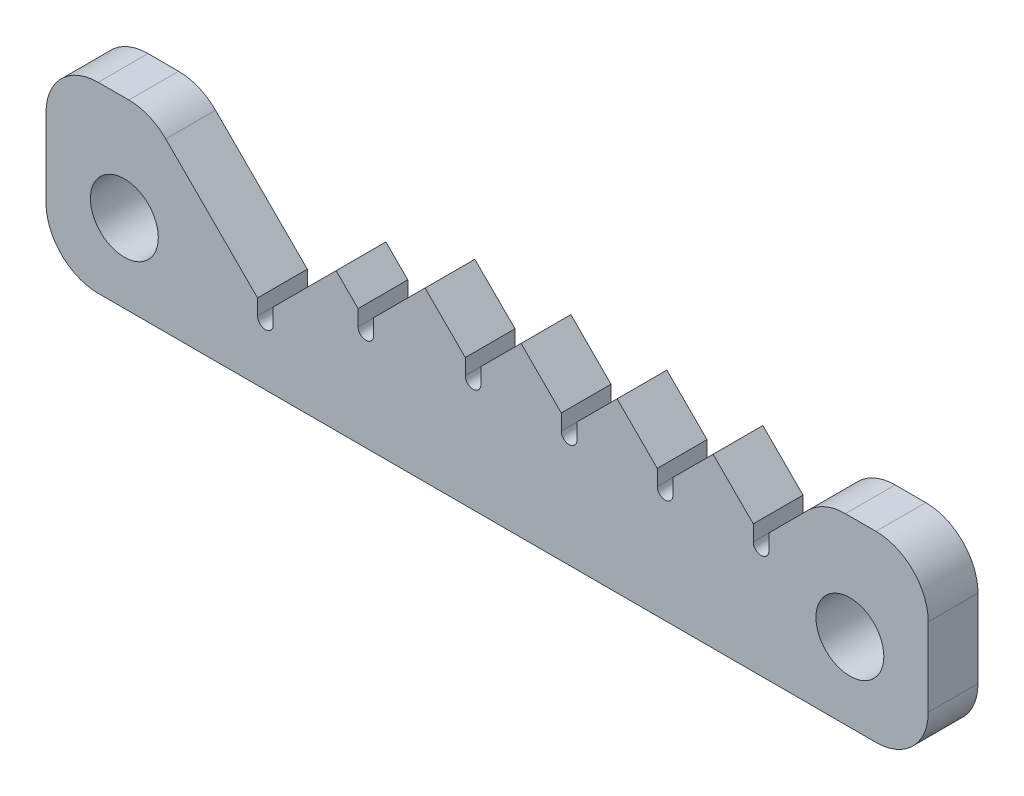
SolidWorks part; units mm, degrees
ref_plane "Alzado" through (0, 0, 0) normal (0, 0, 1) x (1, 0, 0)
ref_plane "Planta" through (0, 0, 0) normal (0, 1, 0) x (1, 0, 0)
ref_plane "Vista lateral" through (0, 0, 0) normal (1, 0, 0) x (0, 0, -1)
sketch "Croquis9" plane through (0, 0, 0) normal (0, 0, 1) x (1, 0, 0)
  line L57 (-5, 20) -> (-15.5, 9.5)
  line L58 (-15.5, 9.5) -> (-15.5, 6.5)
  line L59 (-18.5, 6.5) -> (-18.5, 9.5)
  line L60 (-18.5, 9.5) -> (-26.19, 17.19)
  line L61 (-26.19, 17.19) -> (-33.88, 9.5)
  line L62 (-33.88, 9.5) -> (-33.88, 6.5)
  line L63 (-36.88, 6.5) -> (-36.88, 9.5)
  line L64 (-36.88, 9.5) -> (-44.57, 17.19)
  line L65 (-44.57, 17.19) -> (-52.26, 9.5)
  line L66 (-52.26, 9.5) -> (-52.26, 6.5)
  line L67 (-55.26, 6.5) -> (-55.26, 9.5)
  line L68 (-55.26, 9.5) -> (-62.95, 17.19)
  line L69 (-62.95, 17.19) -> (-70.64, 9.5)
  line L70 (-70.64, 9.5) -> (-70.64, 6.5)
  line L71 (-73.64, 6.5) -> (-73.64, 9.5)
  line L72 (-73.64, 9.5) -> (-81.33, 17.19)
  line L96 (-153.91, 20) -> (-133.91, 20)
  line L101 (-5, 20) -> (15, 20)
  line L108 (-110.41, -0.5) -> (-98.3641, 11.5459)
  line L119 (-113.41, -0.5) -> (-133.91, 20)
  line L120 (-113.41, -0.5) -> (-111.91, -2) construction
  line L121 (-73.64, 9.5) -> (-72.14, 8) construction
  line L122 (-72.14, 8) -> (-70.64, 9.5) construction
  line L126 (-92.8181, 17.0919) -> (-111.91, -2) construction
  line L127 (-92.8181, 17.0919) -> (-111.91, 36.1838) construction
  line L128 (-111.91, 36.1838) -> (-131.0019, 17.0919) construction
  line L129 (-111.91, -2) -> (-131.0019, 17.0919) construction
  line L130 (-110.41, -0.5) -> (-111.91, -2) construction
  line L131 (-73.5772, 24.9428) -> (-92.6691, 5.8509) construction
  line L136 (-153.91, -15) -> (15, -15)
  line L137 (-98.3641, 11.5459) -> (-94.1691, 7.3509)
  line L138 (-91.1691, 7.3509) -> (-81.33, 17.19)
  line L139 (-113.41, -0.5) -> (-113.41, -3.5)
  line L140 (-110.41, -0.5) -> (-110.41, -3.5)
  line L141 (-94.1691, 7.3509) -> (-94.1691, 4.3509)
  line L142 (-91.1691, 7.3509) -> (-91.1691, 4.3509)
  line L143 (-73.5772, 24.9428) -> (-92.6691, 44.0347) construction
  line L144 (-92.6691, 44.0347) -> (-111.7609, 24.9428) construction
  line L145 (-92.6691, 5.8509) -> (-111.7609, 24.9428) construction
  line L146 (-147.7937, 65.1782) -> (-166.8856, 46.0863) construction
  line L147 (-147.7937, 65.1782) -> (-166.8856, 84.27) construction
  line L148 (-166.8856, 84.27) -> (-185.9775, 65.1782) construction
  line L149 (-166.8856, 46.0863) -> (-185.9775, 65.1782) construction
  line L150 (-94.1691, 7.3509) -> (-92.6691, 5.8509) construction
  line L151 (-91.1691, 7.3509) -> (-92.6691, 5.8509) construction
  line L152 (-153.91, 20) -> (-153.91, -15)
  line L153 (15, 20) -> (15, -15)
  arc A39 (-18.5, 6.5) -> (-15.5, 6.5) centre (-17, 6.5) ccw
  arc A40 (-36.88, 6.5) -> (-33.88, 6.5) centre (-35.38, 6.5) ccw
  arc A41 (-55.26, 6.5) -> (-52.26, 6.5) centre (-53.76, 6.5) ccw
  arc A42 (-73.64, 6.5) -> (-70.64, 6.5) centre (-72.14, 6.5) ccw
  arc A51 (-113.41, -3.5) -> (-110.41, -3.5) centre (-111.91, -3.5) ccw
  arc A52 (-94.1691, 4.3509) -> (-91.1691, 4.3509) centre (-92.6691, 4.3509) ccw
  circle A53 centre (-138.91, 0) radius 6.5
  circle A54 centre (0, 0) radius 6.5
  dimension "D5" = 35
  dimension "D6" = 15
  dimension "D7" = 128.91
  dimension "D9" = 15
  dimension "D10" = 1.5
  dimension "D12" = 1.5
  dimension "D13" = 1.5
  dimension "D14" = 10.5
  dimension "D11" = 1.5
  dimension "D15" = 10.5
  dimension "D16" = 13
  dimension "D17" = 3
  dimension "D20" = 18.38
  dimension "D21" = 18.38
  dimension "D18" = 3
  dimension "D8" = 3
  dimension "D41" = 3
  dimension "D39" = 13
  dimension "D43" = 15
  dimension "D45" = 13
  dimension "D19" = 3
  dimension "D23" = 18.38
  dimension "D24" = 3
  dimension "D27" = 3
  dimension "D28" = 3
  dimension "D29" = 7.8509
  dimension "D30" = 10
  dimension "D31" = 7.8509
  dimension "D32" = 27
  dimension "D33" = 27
  dimension "D34" = 27
  dimension "D35" = 27
  dimension "D36" = 27
  dimension "D37" = 27
  dimension "D38" = 3
  dimension "D40" = 3
  dimension "D42" = 3
  dimension "D44" = 5
  dimension "D46" = 5
extrude "Saliente-Extruir1" add sketch "Croquis9" along normal mid plane 9.53
fillet "Redondeo1" radius 10 6 edges at (-5, 20, 0) (-133.91, 20, 0) (15, 20, 0) (15, -15, 0) (-153.91, -15, 0) (-153.91, 20, 0)
sketch "Croquis10" plane through (0, 0, 4.765) normal (0, 0, 1) x (1, 0, 0)
  line L0 (-7.9289, 17.0711) -> (-15.5, 9.5) construction
  line L1 (-18.5, 9.5) -> (-26.19, 17.19) construction
  line L2 (-26.19, 17.19) -> (-33.88, 9.5) construction
  line L3 (-36.88, 9.5) -> (-44.57, 17.19) construction
  line L4 (-44.57, 17.19) -> (-52.26, 9.5) construction
  line L5 (-55.26, 9.5) -> (-62.95, 17.19) construction
  line L6 (-62.95, 17.19) -> (-70.64, 9.5) construction
  line L7 (-73.64, 9.5) -> (-81.33, 17.19) construction
  line L8 (-81.33, 17.19) -> (-91.1691, 7.3509) construction
  line L9 (-94.1691, 7.3509) -> (-98.3641, 11.5459) construction
  line L10 (-98.3641, 11.5459) -> (-110.41, -0.5) construction
  line L11 (-113.41, -0.5) -> (-130.9811, 17.0711) construction
  line L12 (-7.9289, 17.0711) -> (-17, 8) construction
  line L13 (-18.5, 9.5) -> (-26.19, 17.19) construction
  line L14 (-26.19, 17.19) -> (-35.38, 8) construction
  line L15 (-36.88, 9.5) -> (-44.57, 17.19) construction
  line L16 (-44.57, 17.19) -> (-53.76, 8) construction
  line L17 (-55.26, 9.5) -> (-62.95, 17.19) construction
  line L18 (-62.95, 17.19) -> (-72.14, 8) construction
  line L19 (-73.64, 9.5) -> (-81.33, 17.19) construction
  line L20 (-81.33, 17.19) -> (-92.6691, 5.8509) construction
  line L21 (-94.1691, 7.3509) -> (-98.3641, 11.5459) construction
  line L22 (-98.3641, 11.5459) -> (-110.41, -0.5) construction
  line L23 (-113.41, -0.5) -> (-130.9811, 17.0711) construction
  line L24 (-111.91, 36.1838) -> (-92.8181, 17.0919) construction
  line L25 (-92.8181, 17.0919) -> (-111.91, -2) construction
  line L26 (-111.91, -2) -> (-131.0019, 17.0919) construction
  line L27 (-131.0019, 17.0919) -> (-111.91, 36.1838) construction
  line L28 (-92.6691, 44.0347) -> (-73.5772, 24.9428) construction
  line L29 (-73.5772, 24.9428) -> (-92.6691, 5.8509) construction
  line L30 (-92.6691, 5.8509) -> (-111.7609, 24.9428) construction
  line L31 (-111.7609, 24.9428) -> (-92.6691, 44.0347) construction
  line L32 (-113.41, -0.5) -> (-111.91, -2) construction
  line L33 (-110.41, -0.5) -> (-111.91, -2) construction
  line L34 (-72.14, 46.1838) -> (-53.0481, 27.0919) construction
  line L35 (-53.0481, 27.0919) -> (-72.14, 8) construction
  line L36 (-72.14, 8) -> (-91.2319, 27.0919) construction
  line L37 (-91.2319, 27.0919) -> (-72.14, 46.1838) construction
  line L38 (-94.1691, 7.3509) -> (-92.6691, 5.8509) construction
  line L39 (-73.64, 9.5) -> (-72.14, 8) construction
  line L40 (-55.26, 9.5) -> (-53.76, 8) construction
  line L41 (-36.88, 9.5) -> (-35.38, 8) construction
  line L42 (-18.5, 9.5) -> (-17, 8) construction
  line L43 (-17, 46.1838) -> (2.0919, 27.0919) construction
  line L44 (2.0919, 27.0919) -> (-17, 8) construction
  line L45 (-17, 8) -> (-36.0919, 27.0919) construction
  line L46 (-36.0919, 27.0919) -> (-17, 46.1838) construction
  line L47 (-53.76, 46.1838) -> (-34.6681, 27.0919) construction
  line L48 (-34.6681, 27.0919) -> (-53.76, 8) construction
  line L49 (-53.76, 8) -> (-72.8519, 27.0919) construction
  line L50 (-72.8519, 27.0919) -> (-53.76, 46.1838) construction
  line L51 (-35.38, 46.1838) -> (-16.2881, 27.0919) construction
  line L52 (-16.2881, 27.0919) -> (-35.38, 8) construction
  line L53 (-35.38, 8) -> (-54.4719, 27.0919) construction
  line L54 (-54.4719, 27.0919) -> (-35.38, 46.1838) construction
  circle A3 centre (-111.91, 17.0919) radius 12 construction
  circle A4 centre (-92.6691, 24.9428) radius 12 construction
  circle A5 centre (-72.14, 27.0919) radius 12 construction
  circle A6 centre (-17, 27.0919) radius 12 construction
  circle A7 centre (-53.76, 27.0919) radius 12 construction
  circle A8 centre (-35.38, 27.0919) radius 12 construction
  point P47 (-70.64, 9.5)
  point P53 (-52.26, 9.5)
  point P57 (-15.5, 8)
  point P59 (-33.88, 8)
  dimension "D1" = 24
  dimension "D2" = 27
  dimension "D3" = 27
  dimension "D4" = 24
  dimension "D7" = 24
  dimension "D10" = 24
  dimension "D13" = 24
  dimension "D16" = 24
  dimension "D5" = 27
  dimension "D6" = 27
  dimension "D8" = 27
  dimension "D9" = 27
  dimension "D11" = 27
  dimension "D12" = 27
  dimension "D14" = 27
  dimension "D15" = 27
  dimension "D17" = 27
  dimension "D18" = 27
